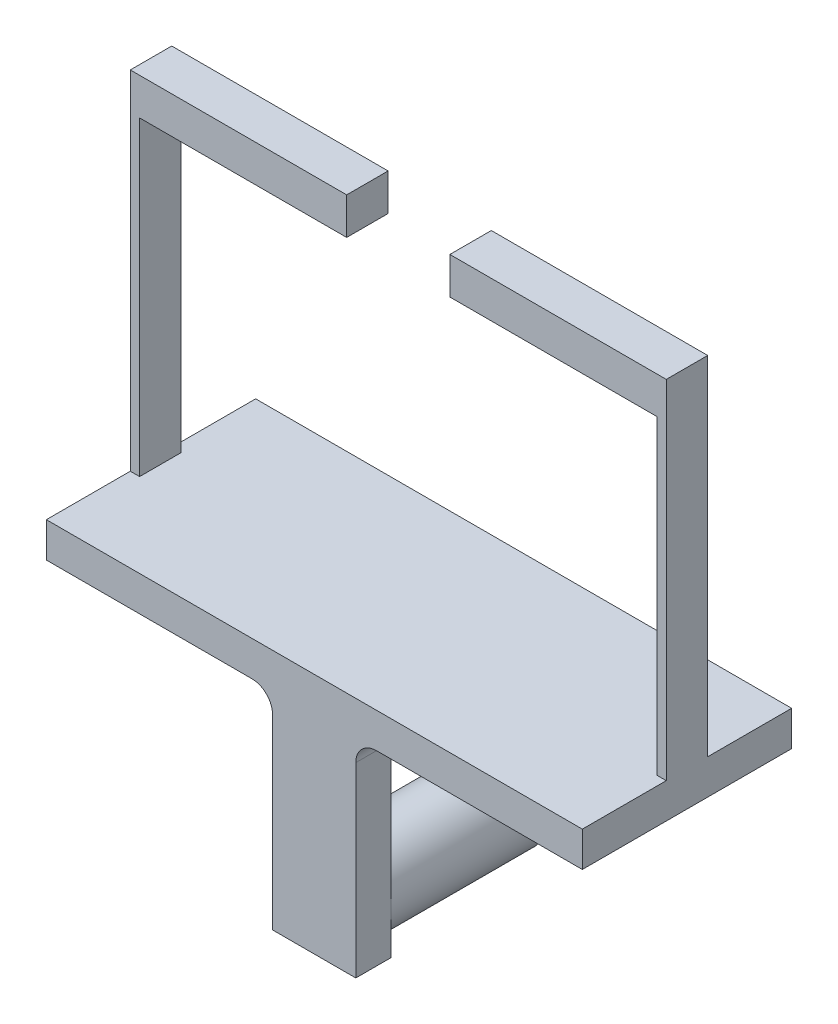
SolidWorks part; units mm, degrees
material "Ti-6Al-4V"
ref_plane "Front Plane" through (0, 0, 0) normal (0, 0, 1) x (1, 0, 0)
ref_plane "Top Plane" through (0, 0, 0) normal (0, 1, 0) x (1, 0, 0)
ref_plane "Right Plane" through (0, 0, 0) normal (1, 0, 0) x (0, 0, -1)
sketch "Sketch6" plane through (0, 0, 0) normal (0, 1, 0) x (1, 0, 0)
  line L1 (-17.2688, 11.9196) -> (-7.0707, 11.9196)
  line L2 (-17.2688, 11.9196) -> (-17.2688, 7.632)
  line L3 (-17.2688, 7.632) -> (-7.0707, 7.632)
  line L4 (-7.0707, 11.9196) -> (-7.0707, 7.632)
  dimension "D1" = 10.1981
  dimension "D2" = 4.2875
extrude "Boss-Extrude3" add sketch "Sketch6" along normal blind 25.4
sketch "Sketch8" plane through (0, 0, -11.9196) normal (0, 0, 1) x (1, 0, 0)
  line L1 (-7.0707, 0) -> (-17.2688, 0) construction
  line L6 (-17.2688, 10.1971) -> (-7.0707, 0) construction
  line L7 (-7.0707, 25.4) -> (-7.0707, 0) construction
  line L8 (-7.0707, 10.1971) -> (-17.2688, 10.1971) construction
  line L9 (-17.2688, 25.4) -> (-17.2688, 0) construction
  line L10 (-7.0707, 0) -> (-7.0707, 10.1971) construction
  line L11 (-7.0707, 10.1971) -> (-17.2688, 0) construction
  circle A0 centre (-12.1698, 5.0985) radius 5.0991
  dimension "D1" = 10.1981
extrude "Boss-Extrude5" add sketch "Sketch8" against normal blind 19.05
sketch "Sketch11" plane through (0, 25.4, 0) normal (0, 1, 0) x (1, 0, 0)
  line L0 (-17.2688, 7.632) -> (-7.0707, 7.632) construction
  line L3 (-44.998, 7.632) -> (20.6965, 7.632)
  line L4 (-44.998, 7.632) -> (-44.998, 33.286)
  line L5 (-44.998, 33.286) -> (20.6965, 33.286)
  line L6 (20.6965, 7.632) -> (20.6965, 33.286)
  dimension "D1" = 25.654
  dimension "D2" = 65.6946
extrude "Boss-Extrude10" add sketch "Sketch11" along normal blind 4.2875
sketch "Sketch16" plane through (0, 29.6875, 0) normal (0, 1, 0) x (1, 0, 0)
  line L3 (20.6965, 33.286) -> (20.6965, 7.632) construction
  line L4 (-44.998, 17.919) -> (-43.855, 17.919)
  line L7 (-44.998, 17.919) -> (-44.998, 22.999)
  line L8 (-44.998, 22.999) -> (-43.855, 22.999)
  line L9 (-43.855, 17.919) -> (-43.855, 22.999)
  line L10 (-44.998, 7.632) -> (20.6965, 7.632) construction
  line L11 (20.6965, 7.632) -> (20.6965, 33.286) construction
  line L13 (20.6965, 22.999) -> (19.5415, 22.999)
  line L14 (20.6965, 22.999) -> (20.6965, 17.919)
  line L15 (20.6965, 17.919) -> (19.5415, 17.919)
  line L16 (19.5415, 22.999) -> (19.5415, 17.919)
  dimension "D1" = 1.143
  dimension "D2" = 1.1551
  dimension "D3" = 5.08
  dimension "D4" = 5.08
extrude "Boss-Extrude11" add sketch "Sketch16" along normal blind 38.0746
sketch "Sketch17" plane through (0, 67.7621, 0) normal (0, 1, 0) x (1, 0, 0)
  line L0 (-44.998, 22.999) -> (-18.4753, 22.999) construction
  line L1 (-44.998, 17.919) -> (-41.8446, 17.919) construction
  line L2 (20.6965, 22.999) -> (-5.8261, 22.999) construction
  line L3 (-44.998, 22.999) -> (-18.4753, 22.999)
  line L4 (-44.998, 22.999) -> (-44.998, 17.919)
  line L5 (-44.998, 17.919) -> (-18.4753, 17.919)
  line L6 (-18.4753, 22.999) -> (-18.4753, 17.919)
  line L7 (20.6965, 17.919) -> (3.53, 17.919) construction
  line L9 (20.6965, 17.919) -> (-5.8261, 17.919)
  line L10 (20.6965, 17.919) -> (20.6965, 22.999)
  line L11 (20.6965, 22.999) -> (-5.8261, 22.999)
  line L12 (-5.8261, 17.919) -> (-5.8261, 22.999)
  dimension "D1" = 26.5227
  dimension "D2" = 26.5227
extrude "Boss-Extrude12" add sketch "Sketch17" along normal blind 4.5212
ref_plane "Plane1" through (-7.0707, 25.4, -11.9196) normal (-1, 0, 0) x (0, 0, 1)
fillet "Fillet2" radius 2.54 1 edges at (-12.1698, 25.4, -11.9196)
fillet "Fillet3" radius 2.54 1 edges at (-17.2688, 25.4, -11.0458)
fillet "Fillet4" radius 2.54 1 edges at (-7.0707, 25.4, -11.0458)
equation "\"baseH\"= 2.5864"
equation "\"baseD\"= 1.01"
equation "\"baseT\" = 0.1688"
equation "\"cylwallH\"= 1"
equation "\"cylwallD\"= 0.4015"
equation "\"cylwallT\"= 0.1688"
equation "\"cylH\"= 1'C"
equation "\"cylD\"= 0.40146"
equation "\"cylT\"= 0.75"
equation "\"sidewallH\"= 0.045"
equation "\"sidewallD\"= 0.2"
equation "\"sidewallT\"= 1.499"
equation "\"horizwallH\"= 0.9992"
equation "\"horizwallD\"= 0.2"
equation "\"horizwallT\"= 0.178"
equation "\"E\"= 16534303"
equation "\"SF\"= 4"
equation "\"W\"= 4 * \"lbs\""
equation "\"Ys\"= 119946"
equation "\"dMAX\"= 0.005"
equation "\"lbs\"= 508"
equation "\"z\"= \"SF\" * \"W\" * ( \"cylT\" / 2 * \"Ys\" )"
equation "\"r\"= ( 4 * ( \"z\" / pi ) ) ^ ( 1 / 3 )"
